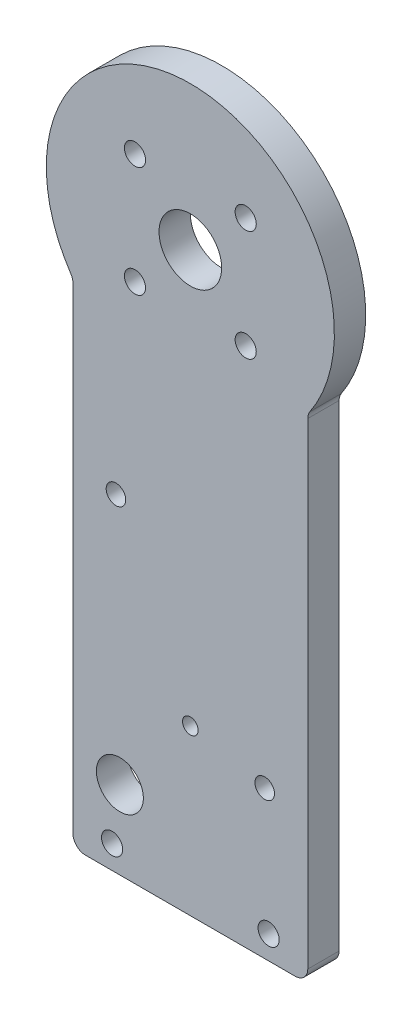
SolidWorks part; units mm, degrees
material "Aleación 1060"
ref_plane "Alzado" through (0, 0, 0) normal (0, 0, 1) x (1, 0, 0)
ref_plane "Planta" through (0, 0, 0) normal (0, 1, 0) x (1, 0, 0)
ref_plane "Vista lateral" through (0, 0, 0) normal (1, 0, 0) x (0, 0, -1)
sketch "Croquis1" plane through (0, 0, 0) normal (0, 0, 1) x (1, 0, 0)
  line L0 (0, 0) -> (-7.0711, -7.0711) construction
  line L1 (0, -18.4) -> (-15, -18.4) construction
  line L2 (-15, -10.6565) -> (-15, -73.6565)
  line L3 (0, -4) -> (0, -18.4) construction
  line L4 (15, -10.6565) -> (15, -73.6565)
  line L5 (-15, -73.6565) -> (15, -73.6565)
  line L6 (0, -73.6565) -> (0, -42.1565) construction
  line L7 (0, -42.1565) -> (12.5, -42.1565) construction
  line L8 (12.5, -42.1565) -> (12.5, -63.2672) construction
  line L9 (12.5, -63.2672) -> (-12.5, -63.2672) construction
  line L10 (-12.5, -63.2672) -> (-12.5, -23.2672) construction
  line L11 (-12.5, -23.2672) -> (12.5, -23.2672) construction
  line L12 (12.5, -23.2672) -> (12.5, -42.1565) construction
  arc A0 (15, -10.6565) -> (-15, -10.6565) centre (0, 0) ccw
  circle A1 centre (-7.0711, -7.0711) radius 1.35
  circle A2 centre (-7.0711, 7.0711) radius 1.35
  circle A3 centre (7.0711, 7.0711) radius 1.35
  circle A4 centre (7.0711, -7.0711) radius 1.35
  circle A5 centre (0, 0) radius 4
  circle A6 centre (-10, -70.6565) radius 1.35
  circle A7 centre (10, -70.6565) radius 1.35
  circle A8 centre (9.5, -54.7912) radius 1.25
  circle A9 centre (-9.5, -31.7912) radius 1.25
  point P14 (0, 0)
  point P27 (15, -42.1565)
  dimension "D1" = 36.8
  dimension "D3" = 2.7
  dimension "D5" = 8
  dimension "D8" = 5
  dimension "D10" = 2.7
  dimension "D14" = 8.524
  dimension "D16" = 19
  dimension "D18" = 2.5
  dimension "D19" = 2.5
  dimension "D2" = 10
  dimension "D6" = 15
  dimension "D7" = 63
  dimension "D9" = 3
  dimension "D11" = 12.5
  dimension "D12" = 40
  dimension "D13" = 25
  dimension "D15" = 3
  dimension "D17" = 23
  dimension "D4" = 4
extrude "Saliente-Extruir1" add sketch "Croquis1" along normal blind 4
fillet "Redondeo1" radius 1.6 4 edges at (-15, -10.6565, 2) (-15, -73.6565, 2) (15, -73.6565, 2) (15, -10.6565, 2)
sketch "Croquis2" plane through (0, 0, 4) normal (0, 0, 1) x (1, 0, 0)
  line L0 (-13.4, -73.6565) -> (13.4, -73.6565) construction
  line L1 (-15, -11.1553) -> (-15, -72.0565) construction
  circle A0 centre (0, -52.6565) radius 1
  circle A1 centre (10, -70.6565) radius 1.35 construction
  circle A2 centre (-9, -63.6565) radius 3
  point P7 (0, -73.6565)
  dimension "D1" = 2
  dimension "D3" = 6
  dimension "D2" = 18
  dimension "D4" = 10
  dimension "D5" = 6
extrude "Cortar-Extruir1" cut sketch "Croquis2" against normal up to vertex (4 mm away)
